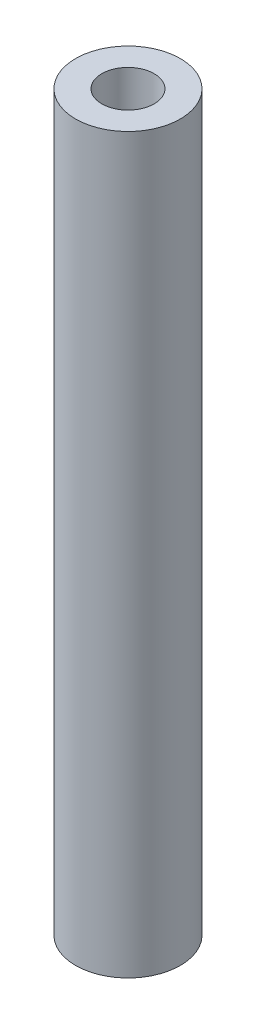
SolidWorks part; units mm, degrees
ref_plane "Front Plane" through (0, 0, 0) normal (0, 0, 1) x (1, 0, 0)
ref_plane "Top Plane" through (0, 0, 0) normal (0, 1, 0) x (1, 0, 0)
ref_plane "Right Plane" through (0, 0, 0) normal (1, 0, 0) x (0, 0, -1)
sketch "Sketch1" plane through (0, 0, 0) normal (0, 1, 0) x (1, 0, 0)
  circle A0 centre (0, 0) radius 2.5
  circle A1 centre (0, 0) radius 1.25
  dimension "D1" = 5
  dimension "D2" = 2.5
extrude "Boss-Extrude1" add sketch "Sketch1" along normal blind 35
